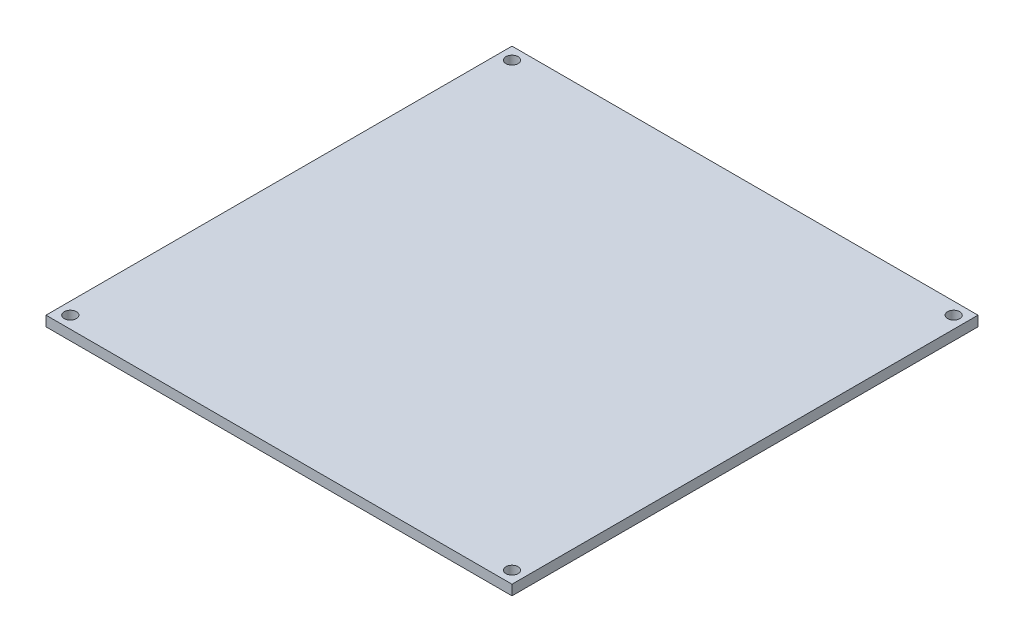
SolidWorks part; units mm, degrees
ref_plane "Front Plane" through (0, 0, 0) normal (0, 0, 1) x (1, 0, 0)
ref_plane "Top Plane" through (0, 0, 0) normal (0, 1, 0) x (1, 0, 0)
ref_plane "Right Plane" through (0, 0, 0) normal (1, 0, 0) x (0, 0, -1)
sketch "Sketch2" plane through (0, 0, 0) normal (0, 1, 0) x (1, 0, 0)
  line L1 (0, 0) -> (230, 0)
  line L2 (0, 0) -> (0, 230)
  line L3 (0, 230) -> (230, 230)
  line L4 (230, 0) -> (230, 230)
  dimension "D1" = 230
  dimension "D2" = 230
extrude "Boss-Extrude1" add sketch "Sketch2" along normal blind 5
sketch "Sketch3" plane through (0, 5, 0) normal (0, 1, 0) x (1, 0, 0)
  circle A0 centre (6, 224) radius 3
  dimension "D1" = 6
extrude "Cut-Extrude1" cut sketch "Sketch3" against normal through all
sketch "Sketch4" plane through (0, 5, 0) normal (0, 1, 0) x (1, 0, 0)
  circle A0 centre (224, 224) radius 3
extrude "Cut-Extrude2" cut sketch "Sketch4" against normal through all
sketch "Sketch5" plane through (0, 5, 0) normal (0, 1, 0) x (1, 0, 0)
  circle A0 centre (6, 6) radius 3
extrude "Cut-Extrude3" cut sketch "Sketch5" against normal through all
sketch "Sketch6" plane through (0, 5, 0) normal (0, 1, 0) x (1, 0, 0)
  circle A0 centre (224, 6) radius 3
extrude "Cut-Extrude4" cut sketch "Sketch6" against normal through all
